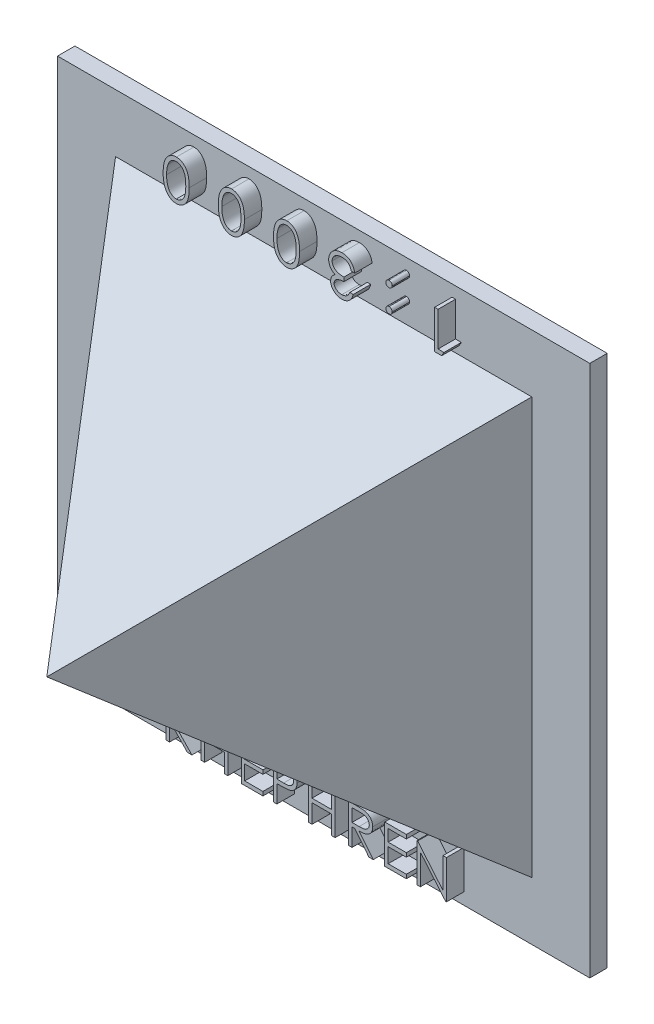
SolidWorks part; units mm, degrees
ref_plane "Plan de face" through (0, 0, 0) normal (0, 0, 1) x (1, 0, 0)
ref_plane "Plan de dessus" through (0, 0, 0) normal (0, 1, 0) x (1, 0, 0)
ref_plane "Plan de droite" through (0, 0, 0) normal (1, 0, 0) x (0, 0, -1)
sketch "Esquisse1" plane through (0, 0, 0) normal (0, 0, 1) x (1, 0, 0)
  line L1 (0, 0) -> (71.72, 0)
  line L2 (0, 0) -> (0, 71.72)
  line L3 (0, 71.72) -> (71.72, 71.72)
  line L4 (71.72, 0) -> (71.72, 71.72)
  dimension "D1" = 71.72
extrude "Boss.-Extru.1" add sketch "Esquisse1" along normal blind 95.9 draft 36.93
sketch "Esquisse3" plane through (0, 0, 0) normal (0, 0, -1) x (-1, 0, 0)
  line L8 (10, -10) -> (10, 81.72)
  line L9 (10, 81.72) -> (-81.72, 81.72)
  line L10 (-81.72, 81.72) -> (-81.72, -10)
  line L11 (-81.72, -10) -> (10, -10)
  line L12 (10, -10) -> (10, 81.72)
  line L13 (10, 81.72) -> (-81.72, 81.72)
  line L14 (-81.72, 81.72) -> (-81.72, -10)
  line L15 (-81.72, -10) -> (10, -10)
  dimension "D1" = 10
extrude "Boss.-Extru.3" add sketch "Esquisse3" along normal blind 3 separate body
sketch "Esquisse2" plane through (0, 0, -3) normal (0, 0, -1) x (-1, 0, 0)
  line L0 (0, 0) -> (-71.72, 0) construction
  line L1 (0, 71.72) -> (0, 0) construction
  circle A0 centre (-35.86, 35.86) radius 23.25
  point P5 (-35.86, 0)
  point P8 (0, 35.86)
  dimension "D1" = 46.5
extrude "Boss.-Extru.2" [suppressed] add sketch "Esquisse2" along normal blind 30
sketch "Esquisse4" plane through (0, 0, 0) normal (0, 0, 1) x (1, 0, 0)
  line L0 (10.86, -8) -> (60.86, -8) construction
  line L1 (10.86, 79.72) -> (60.86, 79.72) construction
  line L2 (0, 0) -> (71.72, 0) construction
  line L3 (81.72, -10) -> (-10, -10) construction
  line L5 (-10, 81.72) -> (81.72, 81.72) construction
  line L6 (71.72, 71.72) -> (0, 71.72) construction
  text T0 "KHEPHREN" font "Century Gothic" height in points 25
  text T1 "1:3000" font "Century Gothic" height in points 25
  point P6 (35.86, 0)
  point P7 (35.86, -8)
  point P12 (35.86, 71.72)
  point P13 (35.86, 79.72)
  dimension "D1" = 2
  dimension "D2" = 2
  dimension "D3" = 50
  dimension "D4" = 50
extrude "Boss.-Extru.4" add sketch "Esquisse4" along normal blind 3
